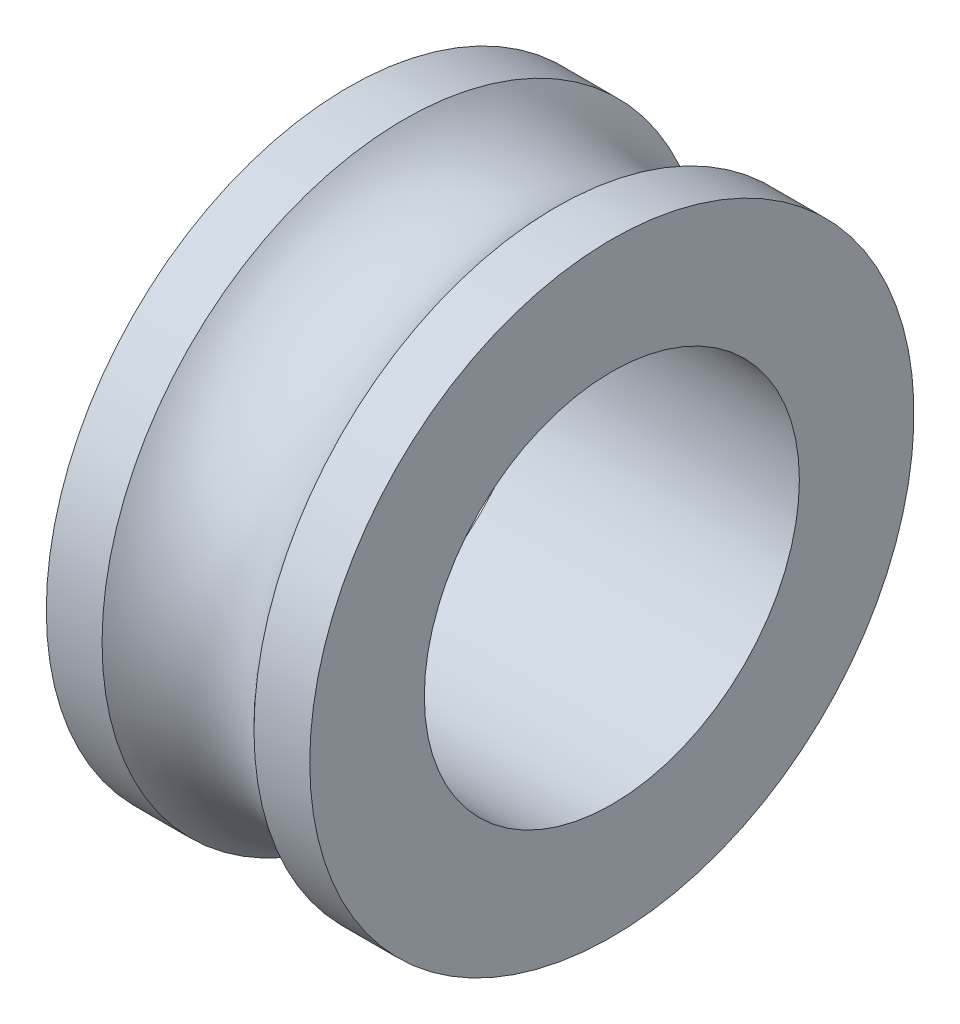
SolidWorks part; units mm, degrees
ref_plane "Front" through (0, 0, 0) normal (0, 0, 1) x (1, 0, 0)
ref_plane "Top" through (0, 0, 0) normal (0, 1, 0) x (1, 0, 0)
ref_plane "Right" through (0, 0, 0) normal (1, 0, 0) x (0, 0, -1)
sketch "草图1" plane through (0, 0, 0) normal (0, 0, 1) x (1, 0, 0)
  line L0 (0, 0) -> (0, 6.644) construction
  line L1 (2.0616, 8.199) -> (3.575, 8.199)
  line L2 (-3.575, 8.199) -> (-2.0616, 8.199)
  line L3 (-3.575, 8.199) -> (-3.575, 5.089)
  line L4 (-3.575, 5.089) -> (3.575, 5.089)
  line L5 (3.575, 8.199) -> (3.575, 5.089)
  line L6 (-3.575, 8.199) -> (3.575, 5.089) construction
  line L7 (-3.575, 5.089) -> (3.575, 8.199) construction
  line L8 (0, 0) -> (9.0007, 0) construction
  arc A0 (-2.0616, 8.199) -> (2.0616, 8.199) centre (0, 10.049) ccw
  dimension "D3" = 2.77
  dimension "D1" = 5.089
  dimension "D2" = 1.85
  dimension "D4" = 3.11
  dimension "D5" = 7.15
revolve "旋转1" add sketch "草图1" angle 360 about L8
